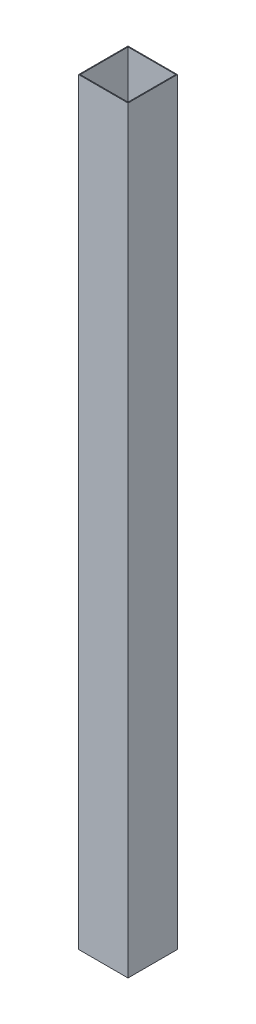
SolidWorks part; units mm, degrees
ref_plane "Front" through (0, 0, 0) normal (0, 0, 1) x (1, 0, 0)
ref_plane "Top" through (0, 0, 0) normal (0, 1, 0) x (1, 0, 0)
ref_plane "Right" through (0, 0, 0) normal (1, 0, 0) x (0, 0, -1)
sketch "Sketch1" plane through (0, 0, 0) normal (0, 1, 0) x (1, 0, 0)
  line L0 (-73.66, 73.66) -> (73.66, 73.66)
  line L1 (-76.2, 76.2) -> (76.2, 76.2)
  line L2 (-76.2, 76.2) -> (-76.2, -76.2)
  line L3 (-76.2, -76.2) -> (76.2, -76.2)
  line L4 (76.2, 76.2) -> (76.2, -76.2)
  line L5 (-76.2, 76.2) -> (76.2, -76.2) construction
  line L6 (-76.2, -76.2) -> (76.2, 76.2) construction
  line L7 (73.66, 73.66) -> (73.66, -73.66)
  line L8 (-73.66, -73.66) -> (73.66, -73.66)
  line L9 (-73.66, 73.66) -> (-73.66, -73.66)
  point P0 (0, 0)
  dimension "D1" = 152.4
  dimension "D2" = 152.4
  dimension "D3" = 2.54
extrude "Boss-Extrude1" add sketch "Sketch1" along normal blind 6019.8
sketch "Sketch2" plane through (0, 0, 76.2) normal (0, 0, 1) x (1, 0, 0)
  line L0 (76.2, 6019.8) -> (76.2, 0) construction
  line L1 (-76.2, 6019.8) -> (76.2, 6019.8)
  line L2 (-76.2, 6019.8) -> (-76.2, 2336.8)
  line L3 (-76.2, 2336.8) -> (76.2, 2336.8)
  line L4 (76.2, 6019.8) -> (76.2, 2336.8)
  dimension "D1" = 2336.8
extrude "Cut-Extrude1" cut sketch "Sketch2" against normal through all
